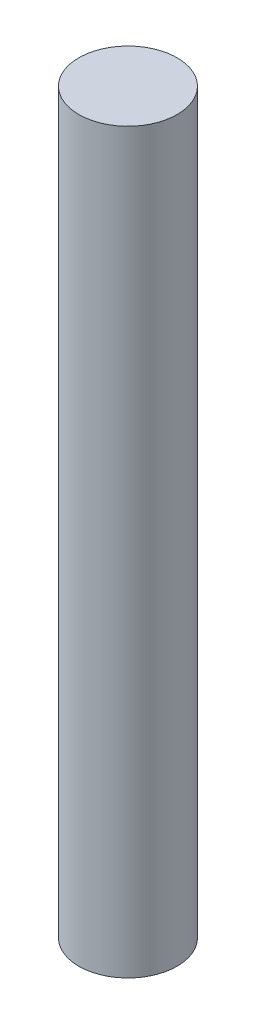
SolidWorks part; units mm, degrees
ref_plane "Front Plane" through (0, 0, 0) normal (0, 0, 1) x (1, 0, 0)
ref_plane "Top Plane" through (0, 0, 0) normal (0, 1, 0) x (1, 0, 0)
ref_plane "Right Plane" through (0, 0, 0) normal (1, 0, 0) x (0, 0, -1)
sketch "Sketch1" plane through (0, 0, 0) normal (0, 1, 0) x (1, 0, 0)
  circle A0 centre (0, 0) radius 2
  dimension "D1" = 4
extrude "Boss-Extrude1" add sketch "Sketch1" along normal blind 30
